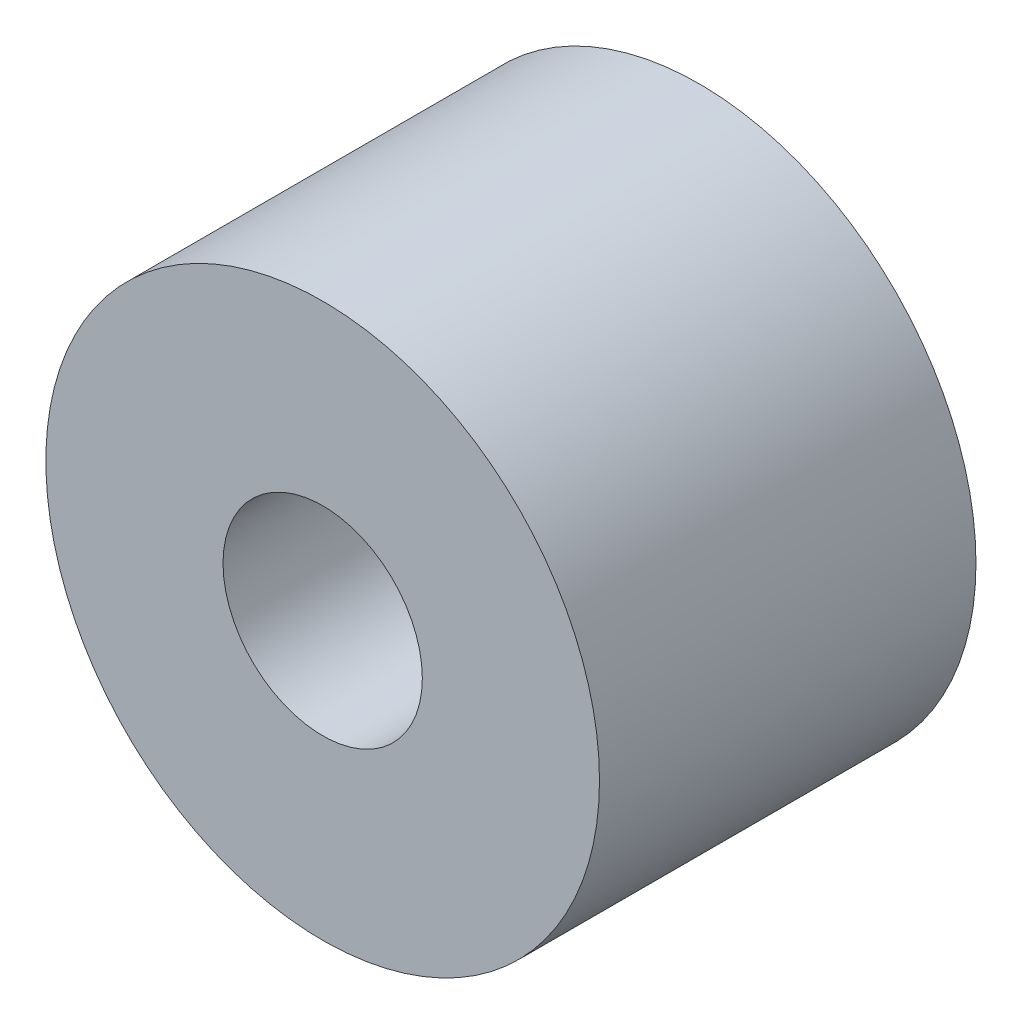
SolidWorks part; units mm, degrees
ref_plane "Plano frontal" through (0, 0, 0) normal (0, 0, 1) x (1, 0, 0)
ref_plane "Plano superior" through (0, 0, 0) normal (0, 1, 0) x (1, 0, 0)
ref_plane "Plano direito" through (0, 0, 0) normal (1, 0, 0) x (0, 0, -1)
sketch "Esboço1" plane through (0, 0, 0) normal (0, 0, 1) x (1, 0, 0)
  circle A0 centre (0, 0) radius 12.5
  circle A1 centre (0, 0) radius 4.5
  dimension "D1" = 9
  dimension "D2" = 25
extrude "Ressalto-extrusão1" add sketch "Esboço1" along normal blind 17
